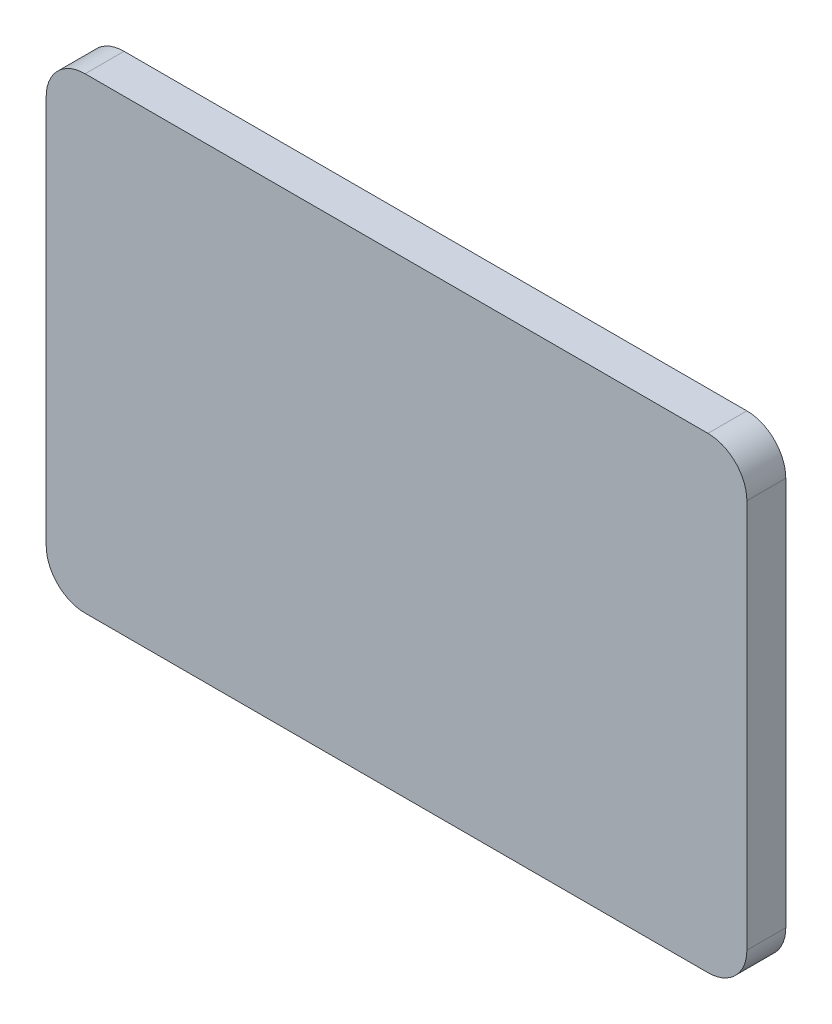
SolidWorks part; units mm, degrees
ref_plane "Frontale" through (0, 0, 0) normal (0, 0, 1) x (1, 0, 0)
ref_plane "Superiore" through (0, 0, 0) normal (0, 1, 0) x (1, 0, 0)
ref_plane "Destro" through (0, 0, 0) normal (1, 0, 0) x (0, 0, -1)
sketch "Schizzo1" plane through (0, 0, 0) normal (0, 0, 1) x (1, 0, 0)
  line L1 (80, -60) -> (-80, -60)
  line L2 (90, -50) -> (90, 50)
  line L3 (80, 60) -> (-80, 60)
  line L4 (-90, -50) -> (-90, 50)
  line L5 (90, -60) -> (-90, 60) construction
  line L6 (90, 60) -> (-90, -60) construction
  arc A0 (-80, 60) -> (-90, 50) centre (-80, 50) ccw
  arc A1 (90, 50) -> (80, 60) centre (80, 50) ccw
  arc A2 (90, -50) -> (80, -60) centre (80, -50) cw
  arc A3 (-80, -60) -> (-90, -50) centre (-80, -50) cw
  point P0 (0, 0)
  dimension "D1" = 10
  dimension "D2" = 120
  dimension "D3" = 180
extrude "Estrusione1" add sketch "Schizzo1" along normal blind 10
